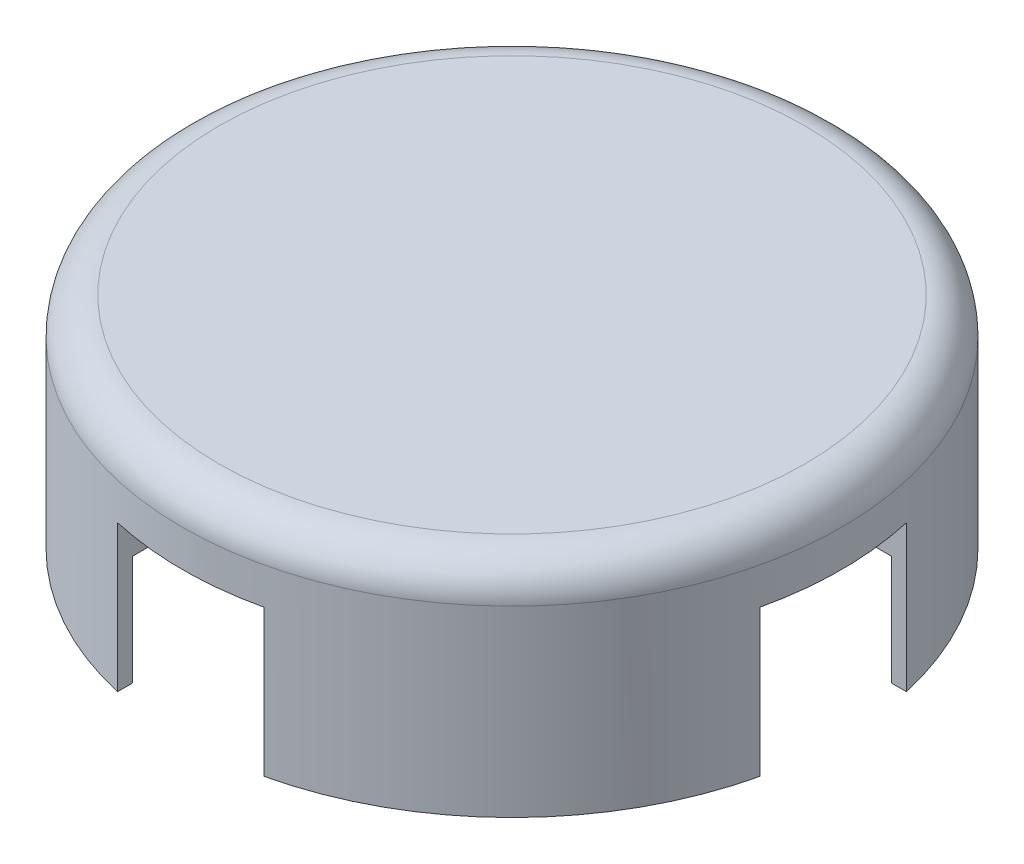
SolidWorks part; units mm, degrees
material "SUS304"
ref_plane "前基準面" through (0, 0, 0) normal (0, 0, 1) x (1, 0, 0)
ref_plane "上基準面" through (0, 0, 0) normal (0, 1, 0) x (1, 0, 0)
ref_plane "右基準面" through (0, 0, 0) normal (1, 0, 0) x (0, 0, -1)
sketch "草圖1" plane through (0, 0, 0) normal (0, 1, 0) x (1, 0, 0)
  circle A0 centre (0, 0) radius 45
  dimension "D1" = 90
extrude "填料-伸長1" add sketch "草圖1" along normal blind 30
sketch "草圖2" plane through (0, 0, 0) normal (0, -1, 0) x (-1, 0, 0)
  circle A0 centre (0, 0) radius 43
  dimension "D1" = 86
extrude "除料-伸長1" cut sketch "草圖2" against normal blind 15
sketch "草圖3" plane through (0, 0, 0) normal (0, -1, 0) x (1, 0, 0)
  line L0 (-47.5, 10) -> (-10, 10)
  line L1 (-10, 10) -> (-10, 47.5)
  line L2 (-10, 47.5) -> (10, 47.5)
  line L3 (10, 47.5) -> (10, 10)
  line L4 (10, 10) -> (47.5, 10)
  line L5 (47.5, 10) -> (47.5, -10)
  line L6 (47.5, -10) -> (10, -10)
  line L7 (10, -10) -> (10, -47.5)
  line L8 (10, -47.5) -> (-10, -47.5)
  line L9 (-10, -47.5) -> (-10, -10)
  line L10 (-10, -10) -> (-47.5, -10)
  line L11 (-47.5, -10) -> (-47.5, 10)
  line L12 (-10, 10) -> (10, -10) construction
  point P2 (0, 0)
  dimension "D1" = 95
  dimension "D2" = 95
  dimension "D3" = 20
extrude "除料-伸長2" cut sketch "草圖3" against normal blind 20
fillet "圓角1" radius 5 1 edges at (0, 30, 45)
hole_wizard "M6 螺紋孔1" positions "草圖4" profile "草圖5" tap size "M6" standard "ISO"
sketch "草圖4" plane through (0, 15, 0) normal (0, -1, 0) x (-1, 0, 0)
  line L0 (21.2132, -21.2132) -> (-21.2132, 21.2132) construction
  line L2 (-21.2132, -21.2132) -> (21.2132, 21.2132) construction
  point P0 (21.2132, -21.2132)
  point P2 (-21.2132, 21.2132)
  point P4 (-21.2132, -21.2132)
  point P6 (21.2132, 21.2132)
  point P16 (0, 0)
  dimension "D1" = 60
  dimension "D2" = 90
sketch "草圖5" plane through (-21.2132, 15, 21.2132) normal (1, 0, 0) x (0, 0, -1)
  line L0 (0, 0) -> (0, 14.5022)
  line L1 (0, 14.5022) -> (2.5, 13)
  line L2 (2.5, 13) -> (2.5, 0)
  line L5 (2.5, 0) -> (0, 0)
  line L10 (0, 14.5022) -> (-2.5, 13) construction
  line L11 (0, -6.35) -> (0, 107.95) construction
  dimension "螺孔鑽直徑" = 5
  dimension "螺孔鑽深度" = 13
  dimension "導頭角度" = 118
cosmetic thread "鑽孔螺紋1" parameters "D1"=8, "D2"=6
cosmetic thread "鑽孔螺紋2" parameters "D1"=8, "D2"=6
cosmetic thread "鑽孔螺紋3" parameters "D1"=8, "D2"=6
cosmetic thread "鑽孔螺紋4" parameters "D1"=8, "D2"=6
hole_wizard "M4 螺紋孔1" positions "草圖6" profile "草圖7" tap size "M4" standard "ISO"
sketch "草圖6" plane through (0, 20, 0) normal (0, -1, 0) x (-1, 0, 0)
  point P0 (0, -30)
  point P2 (0, 30)
  point P4 (30, 0)
  point P6 (-30, 0)
  dimension "D1" = 60
  dimension "D2" = 60
  dimension "D3" = 30
  dimension "D4" = 30
sketch "草圖7" plane through (0, 20, 30) normal (1, 0, 0) x (0, 0, -1)
  line L0 (0, 0) -> (0, 8.9914)
  line L1 (0, 8.9914) -> (1.65, 8)
  line L2 (1.65, 8) -> (1.65, 0)
  line L5 (1.65, 0) -> (0, 0)
  line L10 (0, 8.9914) -> (-1.65, 8) construction
  line L11 (0, -6.35) -> (0, 107.95) construction
  dimension "螺孔鑽直徑" = 3.3
  dimension "螺孔鑽深度" = 8
  dimension "導頭角度" = 118
cosmetic thread "鑽孔螺紋5" parameters "D1"=6, "D2"=4
cosmetic thread "鑽孔螺紋6" parameters "D1"=6, "D2"=4
cosmetic thread "鑽孔螺紋7" parameters "D1"=6, "D2"=4
cosmetic thread "鑽孔螺紋8" parameters "D1"=6, "D2"=4
